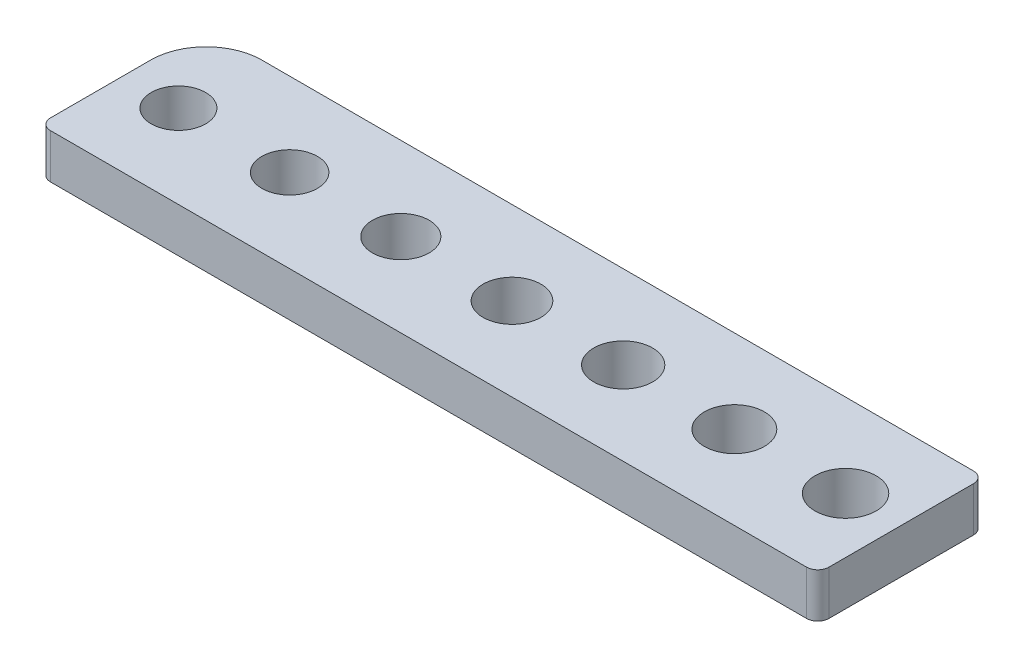
SolidWorks part; units mm, degrees
ref_plane "Front Plane" through (0, 0, 0) normal (0, 0, 1) x (1, 0, 0)
ref_plane "Top Plane" through (0, 0, 0) normal (0, 1, 0) x (1, 0, 0)
ref_plane "Right Plane" through (0, 0, 0) normal (1, 0, 0) x (0, 0, -1)
sketch "Sketch1" plane through (0, 0, 0) normal (0, 1, 0) x (1, 0, 0)
  line L0 (-139.2244, 0) -> (96.0116, 0) construction
  line L1 (0, 92.8454) -> (0, -61.6194) construction
  line L3 (-35, -7.5) -> (35, -7.5)
  line L4 (-35, -7.5) -> (-35, 7.5)
  line L5 (-35, 7.5) -> (35, 7.5)
  line L6 (35, -7.5) -> (35, 7.5)
  line L7 (-35, -7.5) -> (35, 7.5) construction
  line L8 (-35, 7.5) -> (35, -7.5) construction
  circle A0 centre (-30, 0) radius 2.45
  circle A1 centre (-20, 0) radius 2.5
  circle A2 centre (-10, 0) radius 2.55
  circle A3 centre (0, 0) radius 2.6
  circle A4 centre (10, 0) radius 2.65
  circle A9 centre (20, 0) radius 2.7
  circle A10 centre (30, 0) radius 2.75
  point P5 (0, 0)
  dimension "D3" = 5
  dimension "D4" = 10
  dimension "D5" = 10
  dimension "D6" = 5.2
  dimension "D7" = 10
  dimension "D8" = 10
  dimension "D9" = 4.9
  dimension "D10" = 5
  dimension "D11" = 5.1
  dimension "D12" = 5.3
  dimension "D13" = 10
  dimension "D14" = 5.4
  dimension "D15" = 10
  dimension "D16" = 5.5
  dimension "D1" = 70
  dimension "D2" = 15
extrude "Boss-Extrude1" add sketch "Sketch1" along normal blind 4
fillet "Fillet1" radius 5 1 edges at (-35, 2, -7.5)
fillet "Fillet2" radius 1 3 edges at (35, 2, -7.5) (35, 2, 7.5) (-35, 2, 7.5)
